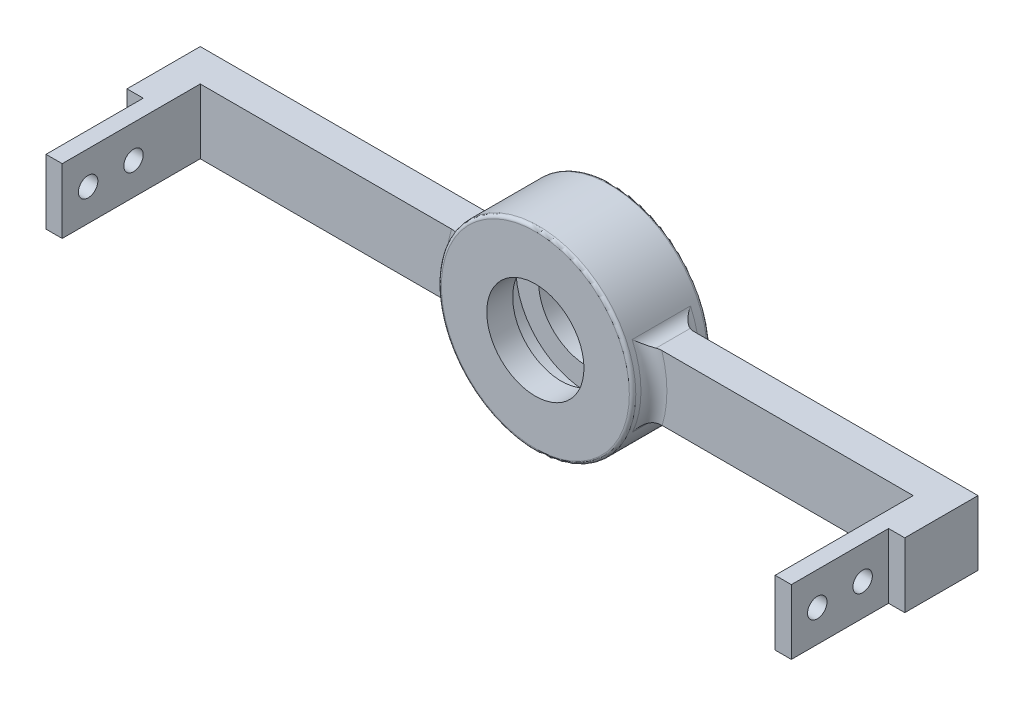
SolidWorks part; units mm, degrees
ref_plane "Front Plane" through (0, 0, 0) normal (0, 0, 1) x (1, 0, 0)
ref_plane "Top Plane" through (0, 0, 0) normal (0, 1, 0) x (1, 0, 0)
ref_plane "Right Plane" through (0, 0, 0) normal (1, 0, 0) x (0, 0, -1)
ref_plane "Plane9" through (0, 0, 37) normal (0, 0, 1) x (1, 0, 0)
sketch "Sketch5" plane through (0, 0, 37) normal (0, 0, 1) x (1, 0, 0)
  circle A0 centre (0, 0) radius 10
  circle A1 centre (0, 0) radius 7.5
sketch "Sketch7" plane through (0, 0, 37) normal (0, 0, 1) x (1, 0, 0)
  circle A0 centre (0, 0) radius 15
extrude "Boss-Extrude2" add sketch "Sketch7" against normal blind 12
sketch "Sketch8" plane through (0, 0, 37) normal (0, 0, 1) x (1, 0, 0)
  circle A0 centre (0, 0) radius 7.5
ref_plane "Plane10" through (0, 0, 33) normal (0, 0, 1) x (1, 0, 0)
sketch "Sketch9" plane through (0, 0, 33) normal (0, 0, 1) x (1, 0, 0)
  circle A0 centre (0, 0) radius 11
extrude "Cut-Extrude1" cut sketch "Sketch9" against normal blind 4
extrude "Cut-Extrude2" cut sketch "Sketch8" against normal blind 20
ref_plane "Plane11" through (15, 0, 0) normal (1, 0, 0) x (0, 0, -1)
sketch "Sketch11" plane through (15, 0, 0) normal (1, 0, 0) x (0, 0, -1)
  line L1 (-33.7033, 5.0704) -> (-28.7033, 5.0704)
  line L2 (-33.7033, 5.0704) -> (-33.7033, -4.9296)
  line L3 (-33.7033, -4.9296) -> (-28.7033, -4.9296)
  line L4 (-28.7033, 5.0704) -> (-28.7033, -4.9296)
  point P4 (0, 0)
  point P5 (-33.7563, 5.6717)
  point P6 (0, 0)
  point P7 (0, 0)
  dimension "D1" = 5
  dimension "D2" = 10
extrude "Boss-Extrude4" add sketch "Sketch11" along normal blind 45 and the other way blind 3
sketch "Sketch14" plane through (0, 0, 33.7033) normal (0, 0, 1) x (1, 0, 0)
  line L0 (14.117, 5.0704) -> (60, 5.0704) construction
  line L1 (55, 5.0704) -> (60, 5.0704)
  line L2 (55, 5.0704) -> (55, -4.9296)
  line L3 (55, -4.9296) -> (60, -4.9296)
  line L4 (60, 5.0704) -> (60, -4.9296)
  line L5 (14.1668, -4.9296) -> (60, -4.9296) construction
  line L6 (60, 5.0704) -> (60, -4.9296) construction
  dimension "D1" = 5
  dimension "D2" = 0
extrude "Boss-Extrude5" add sketch "Sketch14" along normal blind 6.3
sketch "Sketch16" plane through (55, 0, 0) normal (-1, 0, 0) x (0, 0, 1)
  line L0 (40.0033, 5.0704) -> (33.7033, 5.0704) construction
  line L1 (35.0033, 5.0704) -> (40.0033, 5.0704)
  line L2 (35.0033, 5.0704) -> (35.0033, -4.9296)
  line L3 (35.0033, -4.9296) -> (40.0033, -4.9296)
  line L4 (40.0033, 5.0704) -> (40.0033, -4.9296)
  dimension "D1" = 5
sketch "Sketch17" plane through (0, 0, 40.0033) normal (0, 0, 1) x (1, 0, 0)
  line L0 (55, -4.9296) -> (60, -4.9296) construction
  line L1 (55, 5.0704) -> (57.5, 5.0704)
  line L2 (55, 5.0704) -> (55, -4.9296)
  line L3 (55, -4.9296) -> (57.5, -4.9296)
  line L4 (57.5, 5.0704) -> (57.5, -4.9296)
extrude "Boss-Extrude8" add sketch "Sketch17" along normal blind 15
sketch "Sketch20" plane through (57.5, 0, 0) normal (1, 0, 0) x (0, 0, -1)
  line L0 (-40.0033, 5.0704) -> (-40.0033, -4.9296) construction
  line L1 (-55.0033, -4.9296) -> (-55.0033, 5.0704) construction
  circle A0 centre (-44.0033, 0) radius 1.5
  circle A1 centre (-51.0033, 0) radius 1.5
  point P2 (0, 0)
  point P3 (-43.9627, 0)
  point P6 (-49.6821, 0)
  point P7 (-50.2687, 0)
  dimension "D1" = 4
  dimension "D2" = 4
extrude "Cut-Extrude3" cut sketch "Sketch20" against normal blind 15
fillet "Fillet2" radius 2 4 edges at (14.1668, -4.9296, 31.2033) (14.9998, 0.0747, 33.7033) (14.117, 5.0704, 31.2033) (14.9998, 0.0747, 28.7033)
fillet "Fillet7" radius 0.5 1 edges at (15, 0, 37)
fillet "Fillet8" radius 0.5 1 edges at (15, 0, 25)
ref_plane "Plane13" through (0, 0, 0) normal (1, 0, 0) x (0, 0, -1)
mirror "Mirror5" about plane through (0, 0, 0) normal (1, 0, 0) of "Fillet2", "Cut-Extrude3", "Boss-Extrude5", "Boss-Extrude8", "Boss-Extrude4"
sketch "Sketch21" plane through (15, 0, 0) normal (1, 0, 0) x (0, 0, -1)
  line L0 (-35.6728, 2.7933) -> (-37.0421, 2.7933)
  dimension "D1" = 1.3693
